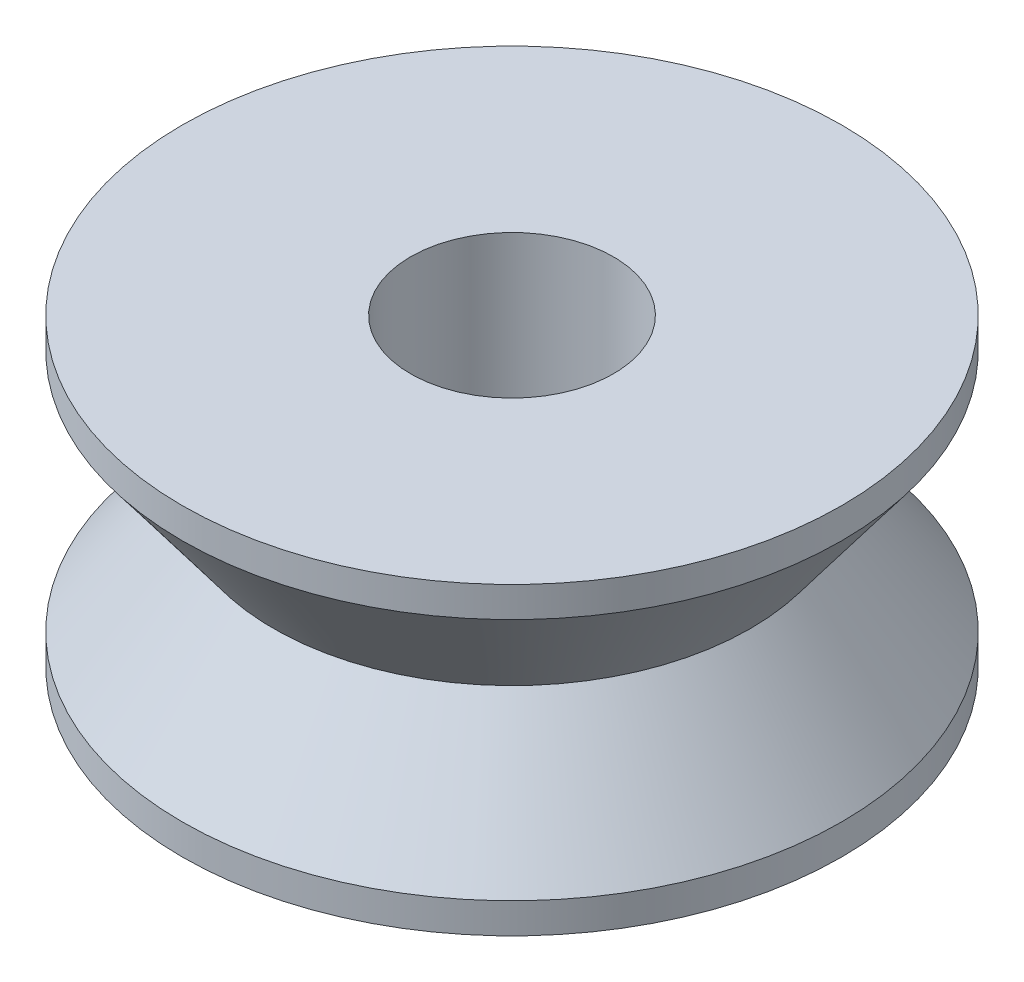
SolidWorks part; units mm, degrees
ref_plane "正面" through (0, 0, 0) normal (0, 0, 1) x (1, 0, 0)
ref_plane "平面" through (0, 0, 0) normal (0, 1, 0) x (1, 0, 0)
ref_plane "右側面" through (0, 0, 0) normal (1, 0, 0) x (0, 0, -1)
sketch "ｽｹｯﾁ1" plane through (0, 0, 0) normal (0, 0, 1) x (1, 0, 0)
  line L0 (0, -3) -> (0, 3)
  line L1 (6.5, 3) -> (6.5, 2.4)
  line L2 (0, 3) -> (6.5, 3)
  line L3 (0, 3) -> (0, -3)
  line L4 (0, -3) -> (6.5, -3)
  line L5 (6.5, 3) -> (6.5, -3) construction
  line L6 (6.5, -3) -> (6.5, -2.4)
  line L7 (6.5, 0) -> (4.7, 0) construction
  line L8 (6.5, 2.4) -> (4.7, 0)
  line L9 (4.7, 0) -> (6.5, -2.4)
  point P2 (0, 0)
  dimension "D1" = 6
  dimension "D2" = 6.5
  dimension "D3" = 2.4
  dimension "D4" = 2.4
  dimension "D5" = 1.8
revolve "回転1" add sketch "ｽｹｯﾁ1" angle 360 about L0
sketch "ｽｹｯﾁ2" plane through (0, 3, 0) normal (0, 1, 0) x (1, 0, 0)
  circle A0 centre (0, 0) radius 2
  dimension "D1" = 4
extrude "ｶｯﾄ - 押し出し1" cut sketch "ｽｹｯﾁ2" against normal blind 10
